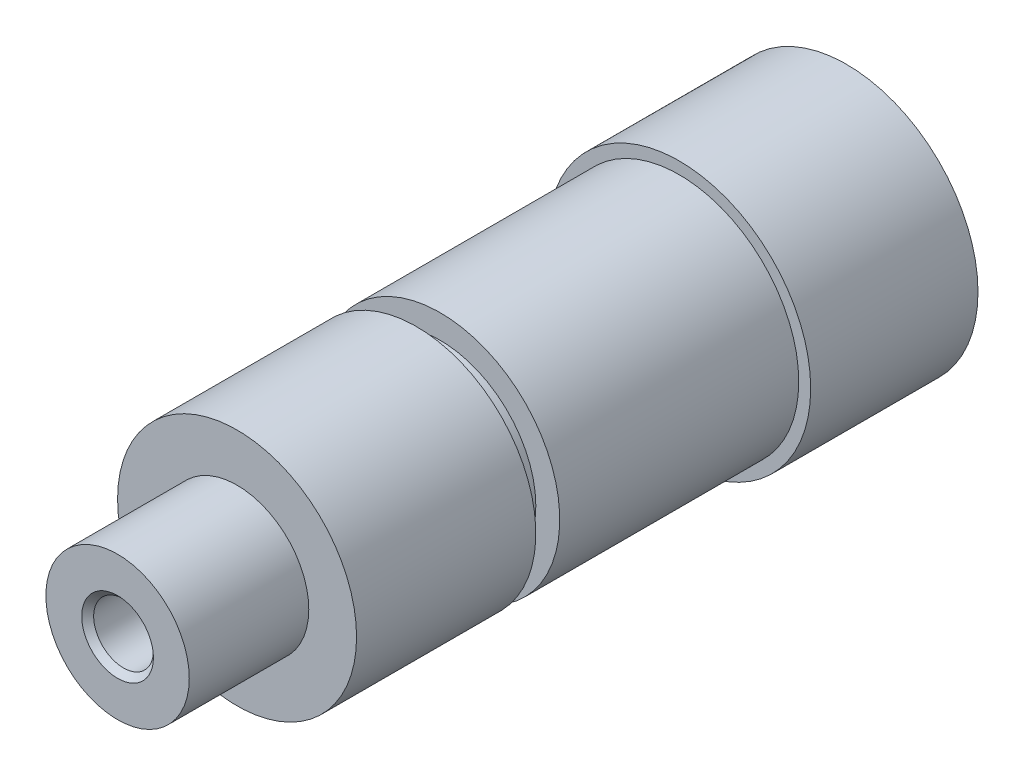
SolidWorks part; units mm, degrees
ref_plane "Face" through (0, 0, 0) normal (0, 0, 1) x (1, 0, 0)
ref_plane "Dessus" through (0, 0, 0) normal (0, 1, 0) x (1, 0, 0)
ref_plane "Droite" through (0, 0, 0) normal (1, 0, 0) x (0, 0, -1)
sketch "Esquisse1" plane through (0, 0, 0) normal (0, 0, 1) x (1, 0, 0)
  circle A0 centre (0, 0) radius 11
  dimension "D1" = 22
extrude "Base-Extrusion" add sketch "Esquisse1" along normal blind 14
sketch "Esquisse2" plane through (0, 0, 14) normal (0, 0, 1) x (1, 0, 0)
  circle A0 centre (0, 0) radius 10
  dimension "D1" = 20
extrude "Boss.-Extru.1" add sketch "Esquisse2" along normal blind 37
sketch "Esquisse3" plane through (0, 0, 0) normal (0, 1, 0) x (1, 0, 0)
  line L0 (10, -34) -> (8, -34)
  line L1 (8, -34) -> (8, -36)
  line L2 (8, -36) -> (10, -36)
  line L3 (10, -36) -> (10, -34)
  line L4 (-11, -14) -> (11, -14) construction
  line L5 (10, -51) -> (10, -14) construction
  line L6 (0, 0) -> (0, -55.4286) construction
  line L7 (0, -14) -> (0, 0) construction
  dimension "D1" = 20
  dimension "D2" = 2
  dimension "D3" = 2
revolve "Enlèvement de matière-Révolution1" cut sketch "Esquisse3" angle 360 about L6
sketch "Esquisse4" plane through (0, 0, 51) normal (0, 0, 1) x (1, 0, 0)
  circle A0 centre (0, 0) radius 6
  dimension "D1" = 12
extrude "Boss.-Extru.2" add sketch "Esquisse4" along normal blind 10
hole_wizard "Trou taraudé M6x1.01" positions "Esquisse6" profile "Esquisse5" tap size "M6x1.0" standard "ISO"
sketch "Esquisse6" plane through (0, 0, 61) normal (0, 0, 1) x (1, 0, 0)
  circle A0 centre (0, 0) radius 6 construction
  point P0 (0, 0)
sketch "Esquisse5" plane through (0, 0, 61) normal (1, 0, 0) x (0, -1, 0)
  line L0 (0, 0) -> (0, 20.5022)
  line L1 (0, 20.5022) -> (2.5, 19)
  line L2 (2.5, 19) -> (2.5, 0.5)
  line L3 (2.5, 0.5) -> (3, 0)
  line L5 (3, 0) -> (0, 0)
  line L6 (-2.5, 0.5) -> (-3, 0) construction
  line L10 (0, 20.5022) -> (-2.5, 19) construction
  line L11 (0, -6.35) -> (0, 107.95) construction
  dimension "Diamètre du perçage" = 5
  dimension "Profondeur du perçage" = 19
  dimension "Diamètre du fraisage entrant" = 6
  dimension "Angle du fraisage entrant" = 90
  dimension "Angle de pointe" = 118
cosmetic thread "Représentation de filetage1" parameters "D1"=16, "D2"=6
